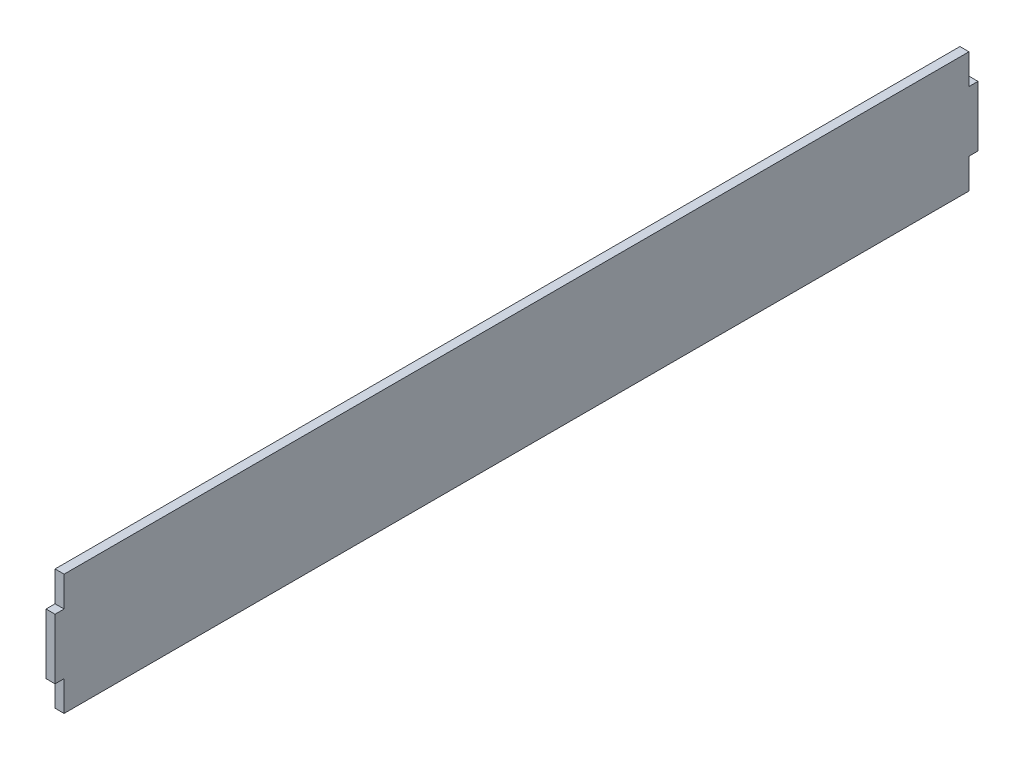
SolidWorks part; units mm, degrees
ref_plane "Front Plane" through (0, 0, 0) normal (0, 0, 1) x (1, 0, 0)
ref_plane "Top Plane" through (0, 0, 0) normal (0, 1, 0) x (1, 0, 0)
ref_plane "Right Plane" through (0, 0, 0) normal (1, 0, 0) x (0, 0, -1)
sketch "Sketch1" plane through (0, 0, 0) normal (1, 0, 0) x (0, 0, -1)
  line L0 (-176.1957, 58.9392) -> (123.8043, 58.9392)
  line L1 (123.8043, 58.9392) -> (123.8043, 48.9392)
  line L2 (123.8043, 48.9392) -> (126.8043, 48.9392)
  line L3 (126.8043, 48.9392) -> (126.8043, 28.9392)
  line L4 (126.8043, 28.9392) -> (123.8043, 28.9392)
  line L5 (123.8043, 28.9392) -> (123.8043, 18.9392)
  line L6 (123.8043, 18.9392) -> (-176.1957, 18.9392)
  line L7 (-176.1957, 18.9392) -> (-176.1957, 28.9392)
  line L8 (-176.1957, 28.9392) -> (-179.1957, 28.9392)
  line L9 (-179.1957, 28.9392) -> (-179.1957, 48.9392)
  line L10 (-179.1957, 48.9392) -> (-176.1957, 48.9392)
  line L11 (-176.1957, 48.9392) -> (-176.1957, 58.9392)
  dimension "D1" = 300
  dimension "D2" = 300
  dimension "D3" = 10
  dimension "D4" = 10
  dimension "D5" = 10
  dimension "D6" = 10
  dimension "D7" = 20
  dimension "D8" = 20
  dimension "D9" = 3
  dimension "D10" = 3
  dimension "D11" = 3
extrude "Boss-Extrude2" add sketch "Sketch1" along normal blind 3
